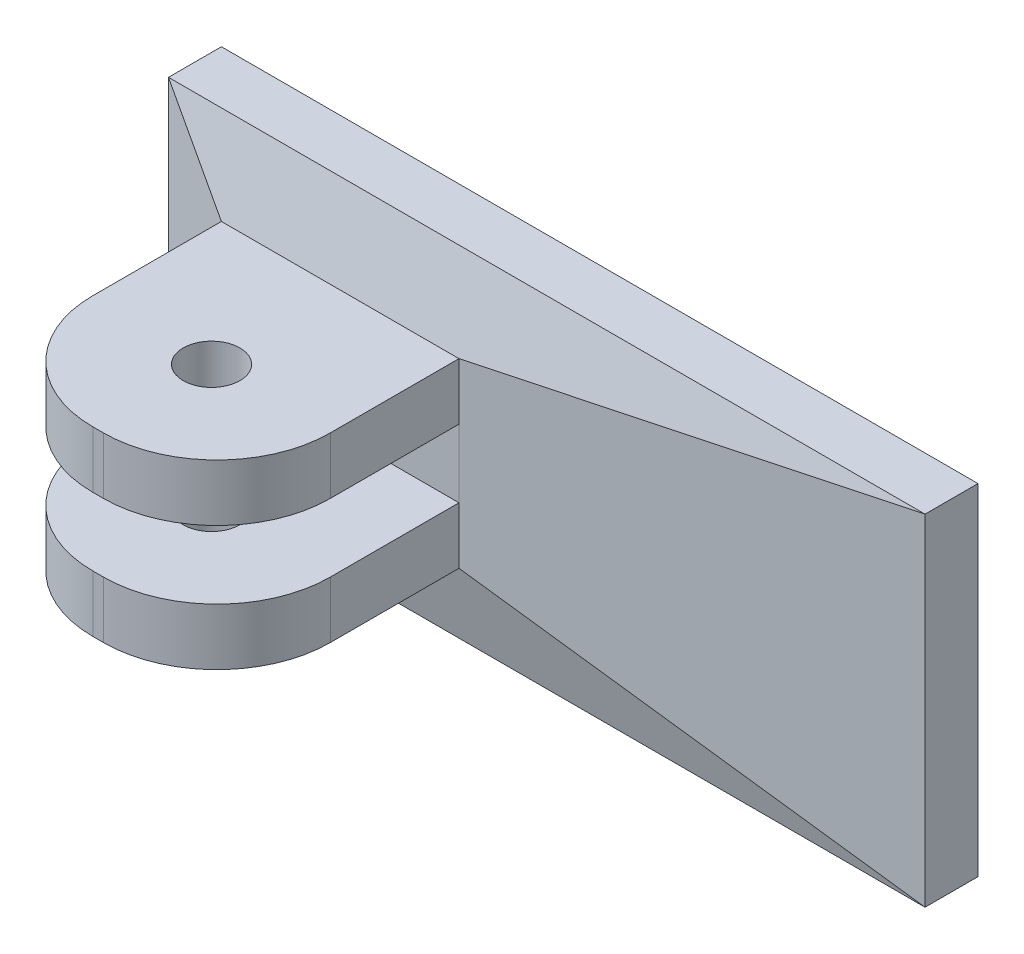
SolidWorks part; units mm, degrees
ref_plane "Front Plane" through (0, 0, 0) normal (0, 0, 1) x (1, 0, 0)
ref_plane "Top Plane" through (0, 0, 0) normal (0, 1, 0) x (1, 0, 0)
ref_plane "Right Plane" through (0, 0, 0) normal (1, 0, 0) x (0, 0, -1)
sketch "Sketch1" plane through (0, 0, 0) normal (0, 0, 1) x (1, 0, 0)
  line L0 (-36.8379, 0) -> (35.7924, 0) construction
  line L1 (-9.658, 0) -> (9.6311, 0) construction
  line L2 (0, 28.0357) -> (0, -21.5283) construction
  line L16 (-23.95, 14.8522) -> (76.05, 14.8522)
  line L17 (-23.95, 14.8522) -> (-23.95, -30.1478)
  line L18 (-23.95, -30.1478) -> (76.05, -30.1478)
  line L19 (76.05, 14.8522) -> (76.05, -30.1478)
  dimension "D1" = 100
  dimension "D2" = 45
extrude "Boss-Extrude1" add sketch "Sketch1" along normal blind 10
sketch "Sketch3" plane through (0, 0, 10) normal (0, 0, 1) x (1, 0, 0)
  line L0 (76.05, 14.8522) -> (-23.95, 14.8522) construction
  line L1 (-13.95, 4.8522) -> (17.45, 4.8522)
  line L2 (-13.95, 4.8522) -> (-13.95, -2.6478)
  line L3 (-13.95, -2.6478) -> (17.45, -2.6478)
  line L4 (17.45, 4.8522) -> (17.45, -2.6478)
  line L5 (-23.95, 14.8522) -> (-23.95, -30.1478) construction
  dimension "D1" = 31.4
  dimension "D2" = 7.5
  dimension "D3" = 10
  dimension "D4" = 10
extrude "Boss-Extrude2" add sketch "Sketch3" along normal blind 5
sketch "Sketch4" plane through (0, -2.6478, 0) normal (0, -1, 0) x (1, 0, 0)
  line L0 (-13.95, 15) -> (-13.95, 27)
  line L1 (1.05, 42) -> (2.45, 42)
  line L2 (17.45, 27) -> (17.45, 15)
  line L3 (-13.95, 15) -> (17.45, 15)
  arc A0 (-13.95, 27) -> (1.05, 42) centre (1.05, 27) cw
  arc A1 (2.45, 42) -> (17.45, 27) centre (2.45, 27) cw
  circle A2 centre (1.7449, 27) radius 3.75
  point P11 (17.45, 42)
  dimension "D2" = 15
  dimension "D3" = 15
  dimension "D1" = 27
extrude "Boss-Extrude3" add sketch "Sketch4" against normal blind 7.5
ref_plane "Plane1" through (0, -7.1478, 0) normal (0, -1, 0) x (-1, 0, 0)
mirror "Mirror1" about plane through (0, -7.1478, 0) normal (0, -1, 0) of "Boss-Extrude3", "Boss-Extrude2"
sketch "Sketch5" plane through (0, -30.1478, 0) normal (0, -1, 0) x (1, 0, 0)
  line L0 (-13.95, 10) -> (-23.95, 7)
  line L1 (-23.95, 10) -> (-23.95, 0) construction
  line L2 (-23.95, 7) -> (-23.95, 10)
  line L3 (-23.95, 10) -> (-13.95, 10)
  line L4 (17.45, 10) -> (76.05, 7)
  line L5 (76.05, 10) -> (76.05, 0) construction
  line L6 (76.05, 7) -> (76.05, 10)
  line L7 (76.05, 10) -> (17.45, 10)
  dimension "D1" = 3
  dimension "D2" = 3
extrude "Cut-Extrude1" cut sketch "Sketch5" against normal blind 45
sketch "Sketch6" plane through (-23.95, 0, 0) normal (-1, 0, 0) x (0, 0, 1)
  line L0 (7, 14.8522) -> (10, 4.8522)
  line L1 (10, 4.8522) -> (10, 14.8522)
  line L2 (10, 14.8522) -> (7, 14.8522)
  line L3 (10, -19.1478) -> (7, -30.1478)
  line L4 (7, -30.1478) -> (10, -30.1478)
  line L5 (10, -30.1478) -> (10, -19.1478)
extrude "Cut-Extrude2" cut sketch "Sketch6" against normal blind 100
